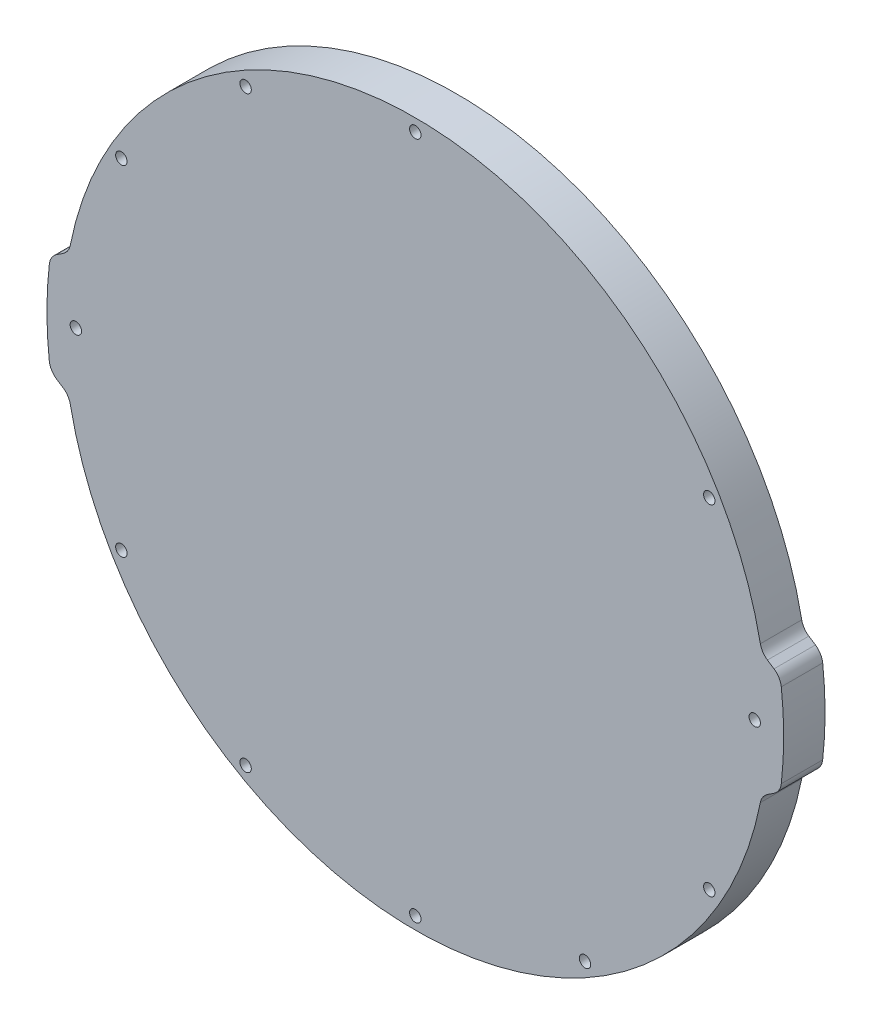
SolidWorks part; units mm, degrees
material "Acrylic (Medium-high impact)"
ref_plane "Front Plane" through (0, 0, 0) normal (0, 0, 1) x (1, 0, 0)
ref_plane "Top Plane" through (0, 0, 0) normal (0, 1, 0) x (1, 0, 0)
ref_plane "Right Plane" through (0, 0, 0) normal (1, 0, 0) x (0, 0, -1)
sketch "Sketch1" plane through (0, 0, 0) normal (0, 0, 1) x (1, 0, 0)
  line L0 (-113.03, 0) -> (113.03, 0) construction
  line L1 (0, -113.03) -> (0, 113.03) construction
  line L2 (-111.9979, 15.24) -> (-106.2558, 19.05)
  line L3 (111.9979, 15.24) -> (106.2558, 19.05)
  line L4 (-111.9979, -15.24) -> (-106.2558, -19.05)
  line L5 (111.9979, -15.24) -> (106.2558, -19.05)
  arc A0 (-111.9979, 15.24) -> (-111.9979, -15.24) centre (0, 0) ccw
  arc A1 (-106.2558, 19.05) -> (-106.2558, -19.05) centre (0, 0) ccw construction
  circle A2 centre (0, 0) radius 104.14 construction
  circle A5 centre (0, 104.14) radius 1.75
  arc A19 (111.9979, 15.24) -> (-111.9979, 15.24) centre (0, 0) ccw construction
  arc A20 (111.9979, -15.24) -> (111.9979, 15.24) centre (0, 0) ccw
  arc A21 (-111.9979, -15.24) -> (111.9979, -15.24) centre (0, 0) ccw construction
  arc A22 (106.2558, 19.05) -> (-106.2558, 19.05) centre (0, 0) ccw
  arc A23 (106.2558, -19.05) -> (106.2558, 19.05) centre (0, 0) ccw construction
  arc A24 (-106.2558, -19.05) -> (106.2558, -19.05) centre (0, 0) ccw
  circle A25 centre (0, 0) radius 88.9 construction
  circle A29 centre (52.07, 90.1879) radius 1.75
  circle A30 centre (90.1879, 52.07) radius 1.75
  circle A31 centre (104.14, 0) radius 1.75
  circle A32 centre (90.1879, -52.07) radius 1.75
  circle A33 centre (52.07, -90.1879) radius 1.75
  circle A34 centre (0, -104.14) radius 1.75
  circle A35 centre (-52.07, -90.1879) radius 1.75
  circle A36 centre (-90.1879, -52.07) radius 1.75
  circle A37 centre (-104.14, 0) radius 1.75
  circle A38 centre (-90.1879, 52.07) radius 1.75
  circle A39 centre (-52.07, 90.1879) radius 1.75
  point P1 (0, 0)
  point P3 (-104.7857, 2.5693)
  dimension "D2" = 208.28
  dimension "D3" = 215.9
  dimension "D4" = 226.06
  dimension "D5" = 3.5
  dimension "D6" = 177.8
  dimension "D7" = 12
  dimension "D9" = 19.05
  dimension "D10" = 15.24
extrude "Boss-Extrude1" add sketch "Sketch1" along normal mid plane 12.7
fillet "Fillet1" radius 5.08 8 edges at (-111.9979, 15.24, 0) (-106.2558, 19.05, 0) (-111.9979, -15.24, 0) (-106.2558, -19.05, 0) (111.9979, -15.24, 0) (106.2558, -19.05, 0) (111.9979, 15.24, 0) (106.2558, 19.05, 0)
